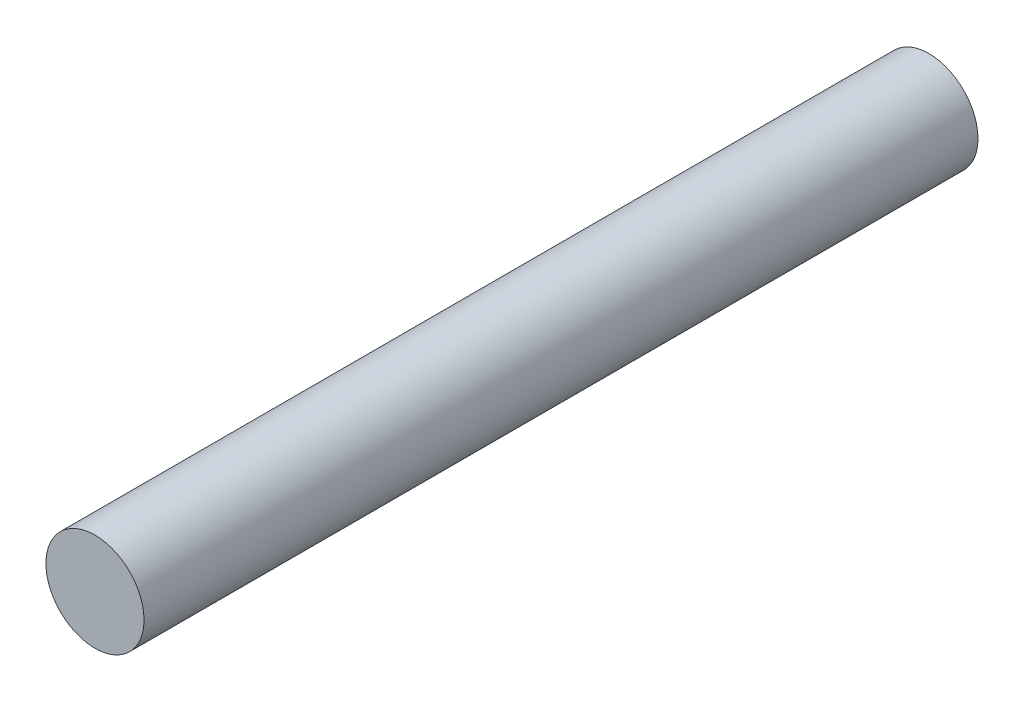
SolidWorks part; units mm, degrees
ref_plane "Front Plane" through (0, 0, 0) normal (0, 0, 1) x (1, 0, 0)
ref_plane "Top Plane" through (0, 0, 0) normal (0, 1, 0) x (1, 0, 0)
ref_plane "Right Plane" through (0, 0, 0) normal (1, 0, 0) x (0, 0, -1)
sketch "Sketch2" plane through (0, 0, 0) normal (0, 0, 1) x (1, 0, 0)
  circle A0 centre (0, 0) radius 1.25
  dimension "D1" = 2.5
sketch "Sketch3" plane through (0, 0, 0) normal (0, 0, 1) x (1, 0, 0)
  line L5 (-2, 2) -> (2, 2) construction
  line L6 (-2, 2) -> (-2, -2) construction
  line L7 (-2, -2) -> (2, -2) construction
  line L8 (2, 2) -> (2, -2) construction
  circle A0 centre (0, 0) radius 2
  point P4 (0, 2)
  point P6 (-2, 0)
  dimension "D1" = 4
extrude "Boss-Extrude1" add sketch "Sketch3" along normal blind 34
equation "\"length\"=34"
equation "\"D1@Boss-Extrude1\"=\"length\""
